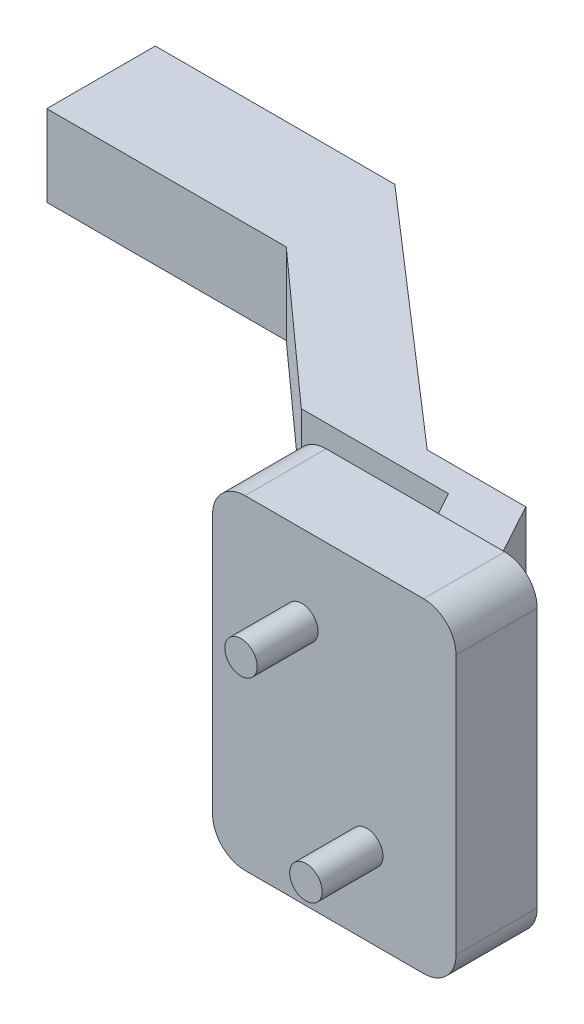
SolidWorks part; units mm, degrees
ref_plane "Plan de face" through (0, 0, 0) normal (0, 0, 1) x (1, 0, 0)
ref_plane "Plan de dessus" through (0, 0, 0) normal (0, 1, 0) x (1, 0, 0)
ref_plane "Plan de droite" through (0, 0, 0) normal (1, 0, 0) x (0, 0, -1)
sketch "Esquisse1" plane through (0, 0, 0) normal (0, 0, 1) x (1, 0, 0)
  circle A0 centre (-2, 5) radius 1
  circle A1 centre (2, -5) radius 1
  point P0 (0, 0)
extrude "Boss.-Extru.1" add sketch "Esquisse1" along normal blind 3.75
sketch "Esquisse2" plane through (0, 0, 0) normal (0, 0, 1) x (1, 0, 0)
  line L1 (-5.5, -10) -> (5.5, -10)
  line L2 (-7.5, -8) -> (-7.5, 8)
  line L3 (-5.5, 10) -> (5.5, 10)
  line L4 (7.5, -8) -> (7.5, 8)
  arc A0 (-7.5, -8) -> (-5.5, -10) centre (-5.5, -8) ccw
  arc A1 (5.5, -10) -> (7.5, -8) centre (5.5, -8) ccw
  arc A2 (7.5, 8) -> (5.5, 10) centre (5.5, 8) ccw
  arc A3 (-7.5, 8) -> (-5.5, 10) centre (-5.5, 8) cw
  point P0 (0, 0)
  dimension "D1" = 2
extrude "Boss.-Extru.2" add sketch "Esquisse2" against normal blind 5
sketch "Esquisse3" plane through (0, 0, 0) normal (0, 1, 0) x (1, 0, 0)
  line L0 (-2, 5) -> (2, 5)
  line L1 (5.5, 5) -> (-5.5, 5) construction
  line L2 (0, 5) -> (0, 0)
  line L3 (2, 5) -> (-3.7553, 15.554)
  line L4 (-3.7553, 15.554) -> (-15.9082, 15.554)
  line L5 (-2, 5) -> (-6.8385, 13.8727)
  line L6 (-6.8385, 13.8727) -> (-15.9082, 13.8727)
  line L7 (-15.9082, 13.8727) -> (-15.9082, 15.554)
  point P5 (0, 5)
extrude "Boss.-Extru.3" add sketch "Esquisse3" along normal blind 2.5 and the other way blind 2.5 contours L7 L6 L5 L0 L3 L4
sketch "Esquisse4" plane through (0, -2.5, 0) normal (0, -1, 0) x (1, 0, 0)
  line L0 (-9.8318, -15.554) -> (-24.9985, -28.7251)
  line L1 (-3.7553, -15.554) -> (-15.9082, -15.554) construction
  line L2 (-24.9985, -28.7251) -> (-74.9985, -28.7251)
  line L3 (-15.9082, -13.8727) -> (-24.9985, -22.0394)
  line L4 (-24.9985, -22.0394) -> (-74.9985, -22.0394)
  line L5 (-74.9985, -22.0394) -> (-74.9985, -28.7251)
  line L6 (-15.9082, -13.8727) -> (-9.8318, -15.554)
extrude "Boss.-Extru.4" add sketch "Esquisse4" against normal up to vertex
sketch "Esquisse6" plane through (0, 0, -28.7251) normal (0, 0, -1) x (-1, 0, 0)
  line L0 (39.7529, -2.5) -> (39.7529, 2.5)
  line L1 (74.9985, -2.5) -> (24.9985, -2.5) construction
  line L2 (74.9985, 2.5) -> (24.9985, 2.5) construction
  line L3 (39.7529, 2.5) -> (50.6378, 9.8806)
  line L4 (50.6378, 9.8806) -> (75.6389, 6.1903)
  line L5 (75.6389, 6.1903) -> (75.6389, -4.916)
  line L6 (75.6389, -4.916) -> (39.7529, -8.6009)
  line L7 (39.7529, -8.6009) -> (39.7529, -2.5)
extrude "Enlèv. mat.-Extru.1" cut sketch "Esquisse6" against normal blind 10
